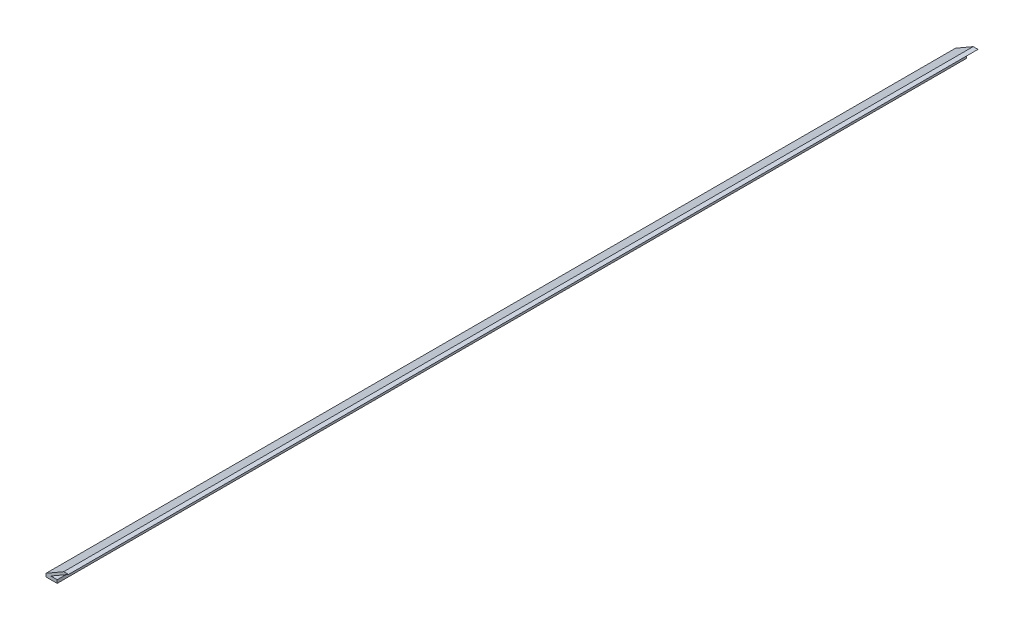
SolidWorks part; units mm, degrees
material "1023 Tôle d'acier au carbone (SS)"
ref_plane "Plan de face" through (0, 0, 0) normal (0, 0, 1) x (1, 0, 0)
ref_plane "Plan de dessus" through (0, 0, 0) normal (0, 1, 0) x (1, 0, 0)
ref_plane "Plan de droite" through (0, 0, 0) normal (1, 0, 0) x (0, 0, -1)
sketch "Esquisse1" plane through (0, 0, 0) normal (0, 0, 1) x (1, 0, 0)
  line L0 (-12, -79.6978) -> (23, -79.6978)
  line L1 (23, -79.6978) -> (23, -69.6978)
  line L2 (23, -69.6978) -> (3, -69.6978)
  line L8 (3, -69.6978) -> (58.5222, -37.6421)
  line L9 (58.5222, -37.6421) -> (43.5222, -37.6421)
  line L10 (43.5222, -37.6421) -> (-12, -69.6978)
  line L11 (-12, -69.6978) -> (-12, -79.6978)
  dimension "D1" = 35
  dimension "D2" = 20
  dimension "D3" = 15
  dimension "D4" = 30
  dimension "D5" = 10
extrude "Boss.-Extru.1" add sketch "Esquisse1" along normal blind 2850
sketch "Esquisse3" plane through (0, -79.6978, 0) normal (0, -1, 0) x (1, 0, 0)
  line L0 (23, 2850) -> (23, 0) construction
  line L1 (-12, 0) -> (23, 0) construction
  circle A13 centre (14, 90) radius 4
  circle A14 centre (14, 290) radius 4
  circle A15 centre (14, 490) radius 4
  circle A16 centre (14, 690) radius 4
  circle A17 centre (14, 890) radius 4
  circle A18 centre (14, 1090) radius 4
  circle A19 centre (14, 1290) radius 4
  circle A20 centre (14, 1490) radius 4
  circle A21 centre (14, 1690) radius 4
  circle A22 centre (14, 1890) radius 4
  circle A23 centre (14, 2090) radius 4
  circle A24 centre (14, 2290) radius 4
  circle A25 centre (14, 2490) radius 4
  circle A26 centre (14, 2690) radius 4
  dimension "D1" = 9
  dimension "D2" = 90
  dimension "D4" = 8
  dimension "D3" = 14
extrude "Enlèv. mat.-Extru.1" cut sketch "Esquisse3" against normal blind 10
